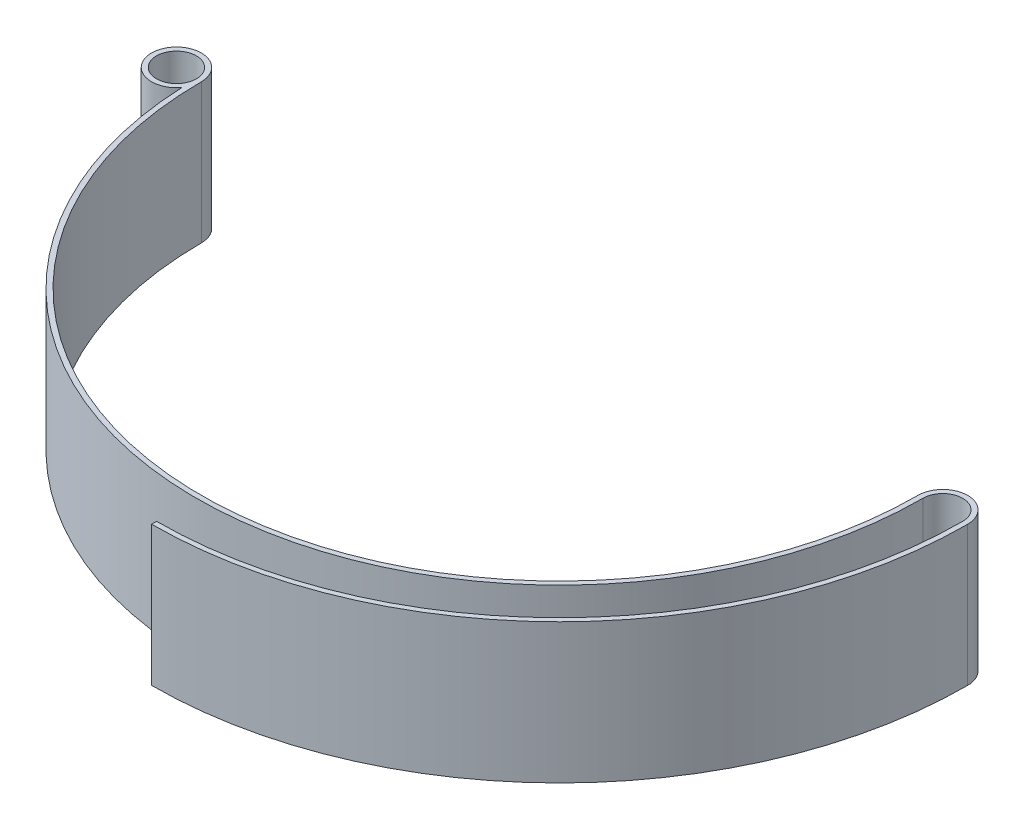
SolidWorks part; units mm, degrees
ref_plane "Front Plane" through (0, 0, 0) normal (0, 0, 1) x (1, 0, 0)
ref_plane "Top Plane" through (0, 0, 0) normal (0, 1, 0) x (1, 0, 0)
ref_plane "Right Plane" through (0, 0, 0) normal (1, 0, 0) x (0, 0, -1)
sketch "Sketch1" plane through (0, 0, 0) normal (0, 1, 0) x (1, 0, 0)
  line L0 (148.69, 0) -> (149.69, 0) construction
  line L1 (76.845, -80.845) -> (76.845, -81.845)
  line L2 (157.69, 0) -> (158.69, 0) construction
  line L3 (76.845, -80.845) -> (76.845, -72.845) construction
  line L4 (149.69, 0) -> (157.69, 0) construction
  circle A0 centre (0, 0) radius 4
  arc A1 (5, 0) -> (148.69, 0) centre (76.845, 0) ccw
  arc A2 (4.0586, -2.9203) -> (149.69, 0) centre (76.845, 0) ccw
  arc A3 (10.4446, -29.9562) -> (149.69, 0) centre (76.845, 0) ccw construction
  arc A5 (5, 0) -> (4.0586, -2.9203) centre (0, 0) ccw
  arc A6 (11.3561, -29.545) -> (148.69, 0) centre (76.845, 0) ccw construction
  arc A7 (148.69, 0) -> (158.69, 0) centre (153.69, 0) cw
  arc A8 (149.69, 0) -> (157.69, 0) centre (153.69, 0) cw
  arc A9 (157.69, 0) -> (76.845, -80.845) centre (76.845, 0) cw
  arc A10 (158.69, 0) -> (76.845, -81.845) centre (76.845, 0) cw
  point P4 (153.69, 5)
  point P31 (5, 0)
  dimension "D1" = 8
  dimension "D5" = 76.845
  dimension "D2" = 153.69
  dimension "D4" = 1
  dimension "D6" = 8
  dimension "D3" = 1
extrude "Boss-Extrude1" add sketch "Sketch1" along normal blind 28
equation "\"L\"=0.153690"
equation "\"w\"=0.028000"
equation "\"Loop_D\"=0.008000"
equation "\"t\"=0.001000"
equation "\"fold_back_L\"=0.076845"
equation "\"D1@Sketch1\"=\"Loop_D\"*1000"
equation "\"D5@Sketch1\"=\"fold_back_L\"*1000"
equation "\"D2@Sketch1\"=\"L\"*1000"
equation "\"D4@Sketch1\"=\"t\"*1000"
equation "\"D6@Sketch1\"=\"Loop_D\"*1000"
equation "\"D1@Boss-Extrude1\"=\"w\"*1000"
